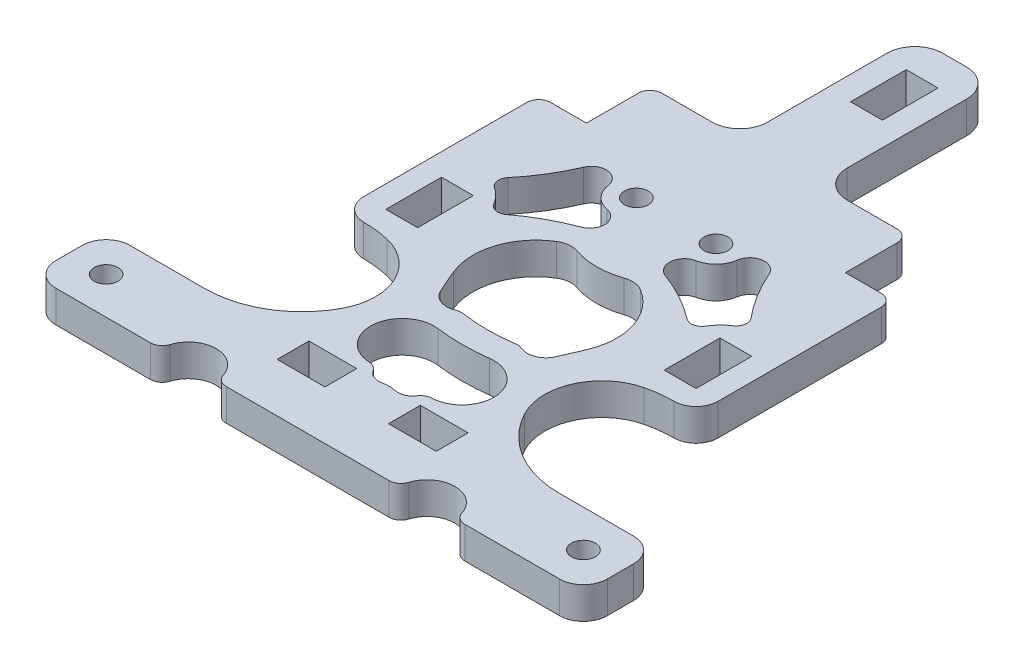
SolidWorks part; units mm, degrees
ref_plane "Plan de face" through (0, 0, 0) normal (0, 0, 1) x (1, 0, 0)
ref_plane "Plan de dessus" through (0, 0, 0) normal (0, 1, 0) x (1, 0, 0)
ref_plane "Plan de droite" through (0, 0, 0) normal (1, 0, 0) x (0, 0, -1)
sketch "Esquisse1" plane through (0, 0, 0) normal (0, 1, 0) x (1, 0, 0)
  line L0 (0, -203.16) -> (0, 154.3311) construction
  line L1 (-20.28, 5) -> (-22.28, 5)
  line L2 (-20.28, 5) -> (-16.28, 5)
  line L3 (-5, 35) -> (-5, 13)
  line L4 (-22.28, 5) -> (-22.28, -122.6773) construction
  line L5 (-22.28, -122.6773) -> (0.6971, -122.6773) construction
  line L6 (2, 30.92) -> (-2, 30.92)
  line L7 (-2, 30.92) -> (-2, 23.92)
  line L8 (-2, 23.92) -> (2, 23.92)
  line L9 (-18.1387, -5) -> (23.5208, -5) construction
  line L10 (-19.5, -10) -> (-15.5, -10)
  line L11 (-19.5, -10) -> (-19.5, -17)
  line L12 (-19.5, -17) -> (-15.5, -17)
  line L13 (-15.5, -10) -> (-15.5, -17)
  line L14 (-10, -36.16) -> (-4, -36.16)
  line L15 (-10, -36.16) -> (-10, -40.16)
  line L16 (-10, -40.16) -> (-4, -40.16)
  line L17 (-4, -36.16) -> (-4, -40.16)
  line L18 (-5, 35) -> (5, 35)
  line L19 (-22.28, 5) -> (-22.28, -37)
  line L21 (-5, 13) -> (-16.28, 13)
  line L22 (-16.28, 13) -> (-16.28, 5)
  line L23 (18.1387, -5) -> (-23.5208, -5) construction
  line L24 (16.28, 13) -> (16.28, 5)
  line L25 (5, 13) -> (16.28, 13)
  line L26 (22.28, 5) -> (22.28, -37)
  line L27 (4, -36.16) -> (4, -40.16)
  line L28 (10, -40.16) -> (4, -40.16)
  line L29 (10, -36.16) -> (10, -40.16)
  line L30 (10, -36.16) -> (4, -36.16)
  line L31 (15.5, -10) -> (15.5, -17)
  line L32 (19.5, -17) -> (15.5, -17)
  line L33 (19.5, -10) -> (19.5, -17)
  line L34 (19.5, -10) -> (15.5, -10)
  line L35 (2, 30.92) -> (2, 23.92)
  line L36 (5, 35) -> (5, 13)
  line L37 (20.28, 5) -> (16.28, 5)
  line L38 (20.28, 5) -> (22.28, 5)
  line L39 (-22.28, -37) -> (-34.66, -37)
  line L40 (-34.66, -37) -> (-34.66, -46.32)
  line L44 (-34.66, -46.32) -> (34.66, -46.32)
  line L45 (-30, -41.66) -> (-34.66, -37) construction
  line L46 (-30, -41.66) -> (-34.66, -46.32) construction
  line L47 (22.28, -37) -> (34.66, -37)
  line L48 (34.66, -37) -> (34.66, -46.32)
  line L49 (30, -41.66) -> (34.66, -37) construction
  line L50 (30, -41.66) -> (34.66, -46.32) construction
  circle A0 centre (-5, 0) radius 1.5
  circle A1 centre (5, 0) radius 1.5
  circle A2 centre (-30, -41.66) radius 1.5
  circle A3 centre (30, -41.66) radius 1.5
  point P38 (0, -40.4225)
  point P40 (0, 35)
  point P49 (0, 23.92)
  point P50 (0, 30.92)
  point P60 (0, -46.32)
  dimension "D2" = 3
  dimension "D22" = 3
  dimension "D1" = 10
  dimension "D3" = 15.28
  dimension "D4" = 4
  dimension "D5" = 5
  dimension "D6" = 6
  dimension "D7" = 7
  dimension "D8" = 2
  dimension "D9" = 26.16
  dimension "D10" = 4
  dimension "D11" = 8
  dimension "D12" = 13.5
  dimension "D13" = 40.92
  dimension "D14" = 5
  dimension "D15" = 40
  dimension "D16" = 6
  dimension "D17" = 5
  dimension "D18" = 18
  dimension "D19" = 20
  dimension "D20" = 1.5
  dimension "D21" = 42
extrude "Boss.-Extru.1" add sketch "Esquisse1" along normal blind 4
sketch "Esquisse2" plane through (0, 4, 0) normal (0, 1, 0) x (1, 0, 0)
  line L0 (0, 18.1178) -> (0, -30.7499) construction
  line L1 (-15.5, -10) -> (-17.1999, -11.6189) construction
  line L3 (-5.938, -4.9112) -> (-5, 0) construction
  line L4 (-5, 0) -> (-9.9511, -0.6975) construction
  line L5 (-14.2621, -6.7262) -> (-15.5, -10) construction
  line L6 (-15.5, -10) -> (-12.1698, -8.9231) construction
  line L7 (15.5, -10) -> (12.1698, -8.9231) construction
  line L8 (14.2621, -6.7262) -> (15.5, -10) construction
  line L9 (5, 0) -> (9.9511, -0.6975) construction
  line L10 (5.938, -4.9112) -> (5, 0) construction
  line L11 (15.5, -10) -> (17.1999, -11.6189) construction
  arc A0 (-14.9975, -7.8435) -> (-13.3216, -9.6032) centre (-17.9572, -12.3402) cw
  arc A1 (-13.3216, -9.6032) -> (-11.3615, -9.9889) centre (-12.1698, -8.9231) ccw
  arc A2 (-11.3615, -9.9889) -> (-5.29, -6.6501) centre (3.022, -28.9549) cw
  arc A8 (-11.6563, 0.0345) -> (-15.2872, -5.867) centre (-33.5294, 9.4241) cw
  arc A9 (-15.2872, -5.867) -> (-14.9975, -7.8435) centre (-14.2621, -6.7262) ccw
  arc A10 (-11.6563, 0.0345) -> (-8.1136, -0.4386) centre (-9.9511, -0.6975) cw
  arc A11 (-8.1136, -0.4386) -> (-5.5899, -3.0885) centre (-5, 0) ccw
  arc A12 (-5.5899, -3.0885) -> (-5.29, -6.6501) centre (-5.938, -4.9112) cw
  circle A13 centre (-5, 0) radius 1.5 construction
  arc A14 (5.5899, -3.0885) -> (5.29, -6.6501) centre (5.938, -4.9112) ccw
  arc A15 (8.1136, -0.4386) -> (5.5899, -3.0885) centre (5, 0) cw
  arc A16 (11.6563, 0.0345) -> (8.1136, -0.4386) centre (9.9511, -0.6975) ccw
  arc A17 (15.2872, -5.867) -> (14.9975, -7.8435) centre (14.2621, -6.7262) cw
  arc A18 (11.6563, 0.0345) -> (15.2872, -5.867) centre (33.5294, 9.4241) ccw
  arc A19 (11.3615, -9.9889) -> (5.29, -6.6501) centre (-3.022, -28.9549) ccw
  arc A20 (13.3216, -9.6032) -> (11.3615, -9.9889) centre (12.1698, -8.9231) cw
  arc A21 (14.9975, -7.8435) -> (13.3216, -9.6032) centre (17.9572, -12.3402) ccw
  dimension "D1" = 5
  dimension "D2" = 3.5
extrude "Enlèv. mat.-Extru.1" cut sketch "Esquisse2" against normal up to next
sketch "Esquisse3" plane through (0, 4, 0) normal (0, 1, 0) x (1, 0, 0)
  line L0 (0, -74.8018) -> (0, 54.5736) construction
  line L1 (-4, -36.16) -> (-5.4516, -38.6743) construction
  line L2 (4, -36.16) -> (5.4516, -38.6743) construction
  line L3 (3.9346, -34.6614) -> (4, -36.16) construction
  line L4 (4, -36.16) -> (2.7349, -35.3541) construction
  line L5 (10, -36.16) -> (4, -36.16) construction
  arc A0 (-3.9346, -34.6614) -> (-2.7349, -35.3541) centre (-4, -36.16) cw
  arc A1 (2.7349, -35.3541) -> (3.9346, -34.6614) centre (4, -36.16) cw
  arc A2 (-2.7349, -35.3541) -> (-0.9018, -36.1339) centre (-1.25, -34.4081) ccw
  arc A3 (2.7349, -35.3541) -> (0.9018, -36.1339) centre (1.25, -34.4081) cw
  arc A4 (0.9018, -36.1339) -> (-0.9018, -36.1339) centre (0, -40.6041) ccw
  arc A5 (-3.9346, -34.6614) -> (-3.2414, -26.699) centre (-3.7601, -30.6652) cw
  arc A6 (3.9346, -34.6614) -> (3.2414, -26.699) centre (3.7601, -30.6652) ccw
  arc A7 (3.2414, -26.699) -> (-3.2414, -26.699) centre (0, -1.9124) cw
  dimension "D5" = 4
  dimension "D1" = 1.5
  dimension "D2" = 2.5
  dimension "D3" = 55
  dimension "D4" = 60
extrude "Enlèv. mat.-Extru.2" cut sketch "Esquisse3" against normal up to next
sketch "Esquisse4" plane through (0, 4, 0) normal (0, 1, 0) x (1, 0, 0)
  line L0 (0, 0) -> (0, -34.64) construction
  arc A0 (-3.2042, -23.4927) -> (3.2042, -23.4927) centre (0, -1.9124) ccw
  arc A1 (-3.2414, -26.699) -> (3.2414, -26.699) centre (0, -1.9124) ccw construction
  arc A2 (-3.2042, -23.4927) -> (-4.2382, -23.6133) centre (-3.4977, -25.4691) ccw
  arc A3 (-4.2382, -23.6133) -> (-7.1847, -22.4339) centre (-5.0915, -21.4748) cw
  arc A4 (-7.1847, -22.4339) -> (-8.4526, -19.5068) centre (62.3097, 9.4075) cw
  arc A5 (-8.4526, -19.5068) -> (-5.2684, -9.7546) centre (-1.1124, -16.5075) cw
  arc A6 (-5.2684, -9.7546) -> (-2.9573, -9.5004) centre (-3.8445, -12.0683) cw
  arc A7 (-2.9573, -9.5004) -> (2.9573, -9.5004) centre (0, -0.9399) ccw
  arc A8 (2.9573, -9.5004) -> (5.2684, -9.7546) centre (3.8445, -12.0683) cw
  arc A10 (7.1847, -22.4339) -> (4.2382, -23.6133) centre (5.0915, -21.4748) cw
  arc A11 (4.2382, -23.6133) -> (3.2042, -23.4927) centre (3.4977, -25.4691) ccw
  arc A12 (5.2684, -9.7546) -> (8.4526, -19.5068) centre (1.1124, -16.5075) cw
  arc A13 (8.4526, -19.5068) -> (7.1847, -22.4339) centre (-62.3097, 9.4075) cw
extrude "Enlèv. mat.-Extru.3" cut sketch "Esquisse4" against normal up to next
fillet "Congé1" radius 3.5 2 edges at (-5, 2, -35) (5, 2, -35)
fillet "Congé2" radius 3.5 2 edges at (5, 2, -13) (-5, 2, -13)
fillet "Congé3" radius 1.5 4 edges at (22.28, 2, -5) (-22.28, 2, -5) (-16.28, 2, -13) (16.28, 2, -13)
sketch "Esquisse7" plane through (0, 4, 0) normal (0, 1, 0) x (1, 0, 0)
  line L0 (-22.28, 3.5) -> (-22.28, -37) construction
  line L1 (-22.28, -37) -> (-34.66, -37) construction
  line L2 (-22.28, -17) -> (-22.28, -37)
  arc A0 (-22.28, -17) -> (-19.5, -19.78) centre (-19.5, -17) ccw
  arc A1 (-19.5, -19.78) -> (-16.1469, -20.1748) centre (-19.5, -34.2169) cw
  arc A2 (-16.1469, -20.1748) -> (-11.4957, -30.5617) centre (-17.814, -27.1561) cw
  arc A3 (-11.4957, -30.5617) -> (-22.28, -37) centre (-22.28, -24.7489) cw
extrude "Enlèv. mat.-Extru.4" cut sketch "Esquisse7" against normal up to next
mirror "Symétrie1" about plane through (0, 0, 0) normal (1, 0, 0) of "Enlèv. mat.-Extru.4"
fillet "Congé4" radius 3 2 edges at (-34.66, 2, 37) (-34.66, 2, 46.32)
fillet "Congé5" radius 3 2 edges at (34.66, 2, 37) (34.66, 2, 46.32)
sketch "Esquisse8" plane through (0, 4, 0) normal (0, 1, 0) x (1, 0, 0)
  line L0 (0, -14.2403) -> (0, -4.5022) construction
  line L1 (-31.66, -46.32) -> (31.66, -46.32) construction
  circle A0 centre (-15, -46.32) radius 3.5
  circle A1 centre (15, -46.32) radius 3.5
  dimension "D2" = 7
  dimension "D1" = 30
extrude "Enlèv. mat.-Extru.5" cut sketch "Esquisse8" against normal up to next
fillet "Congé6" radius 1.5 4 edges at (11.5, 2, 46.32) (18.5, 2, 46.32) (-18.5, 2, 46.32) (-11.5, 2, 46.32)
